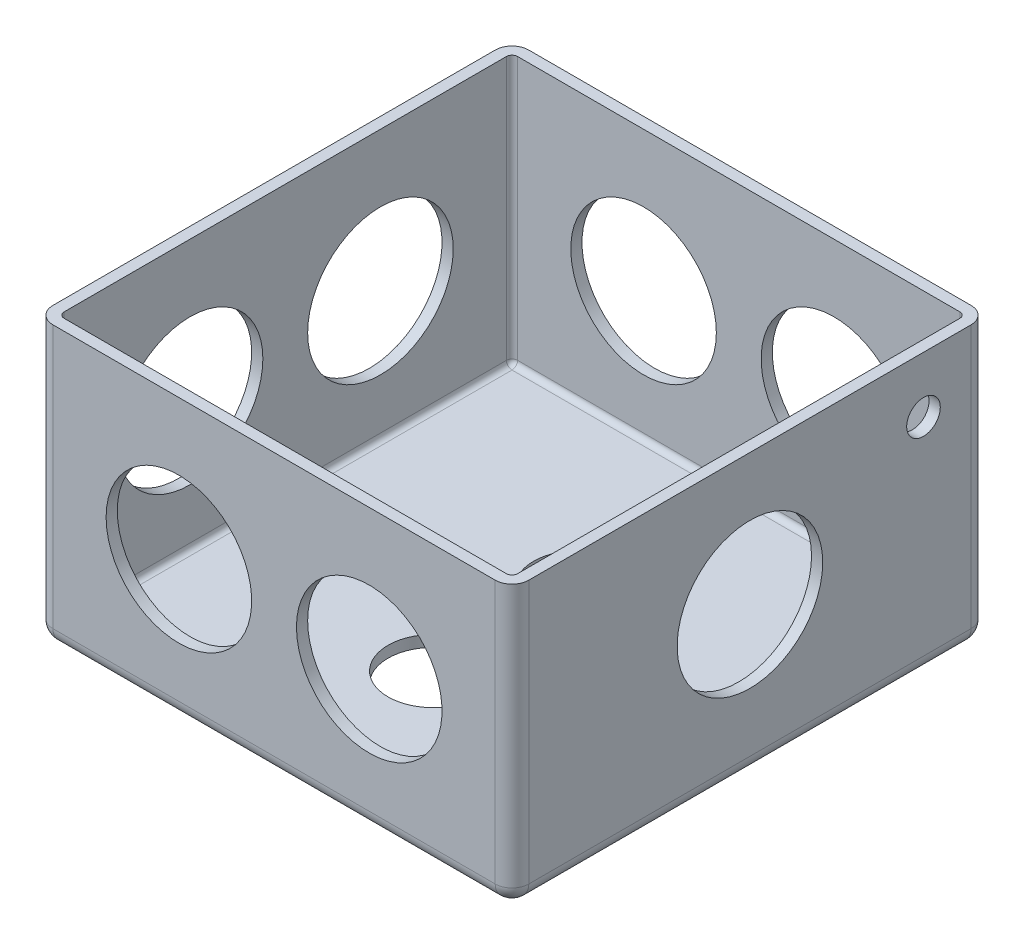
SolidWorks part; units mm, degrees
material "ABS"
ref_plane "Front Plane" through (0, 0, 0) normal (0, 0, 1) x (1, 0, 0)
ref_plane "Top Plane" through (0, 0, 0) normal (0, 1, 0) x (1, 0, 0)
ref_plane "Right Plane" through (0, 0, 0) normal (1, 0, 0) x (0, 0, -1)
sketch "Sketch1" plane through (0, 0, 0) normal (0, 1, 0) x (1, 0, 0)
  line L1 (-42.5, 42.5) -> (42.5, 42.5)
  line L2 (-42.5, 42.5) -> (-42.5, -42.5)
  line L3 (-42.5, -42.5) -> (42.5, -42.5)
  line L4 (42.5, 42.5) -> (42.5, -42.5)
  line L5 (-42.5, 42.5) -> (42.5, -42.5) construction
  line L6 (-42.5, -42.5) -> (42.5, 42.5) construction
  point P0 (0, 0)
  dimension "D1" = 85
  dimension "D2" = 85
extrude "Boss-Extrude1" add sketch "Sketch1" along normal blind 50
fillet "Fillet1" radius 3 8 edges at (-42.5, 25, -42.5) (-42.5, 25, 42.5) (42.5, 25, -42.5) (42.5, 25, 42.5) (-42.5, 0, 0) (0, 0, -42.5) (42.5, 0, 0) (0, 0, 42.5)
shell "Shell2" thickness 2
sketch "Sketch2" plane through (0, 0, 0) normal (0, -1, 0) x (1, 0, 0)
  line L1 (0, 14.1327) -> (0, -11.8673) construction
  circle A2 centre (0, 14.1327) radius 8
  circle A3 centre (0, -11.8673) radius 8
  point P4 (0, 0)
  point P11 (0, 1.1327)
  dimension "D2" = 16
  dimension "D3" = 26
  dimension "D1" = 16
extrude "Cut-Extrude1" cut sketch "Sketch2" against normal blind 50
sketch "Sketch3" plane through (0, 0, 42.5) normal (0, 0, 1) x (1, 0, 0)
  line L0 (17, 25) -> (-17, 25) construction
  line L2 (-42.5, 3) -> (-42.5, 50) construction
  circle A0 centre (-17, 25) radius 13
  circle A1 centre (17, 25) radius 13
  point P3 (0, 25)
  dimension "D2" = 26
  dimension "D3" = 26
  dimension "D1" = 34
  dimension "D4" = 25
  dimension "D5" = 42.5
extrude "Cut-Extrude2" cut sketch "Sketch3" against normal through all both and the other way through all
sketch "Sketch4" plane through (42.5, 0, 0) normal (1, 0, 0) x (0, 0, -1)
  line L0 (-39.5, 50) -> (39.5, 50) construction
  circle A0 centre (0, 26.5) radius 13
  circle A1 centre (30.9979, 40) radius 3
  dimension "D1" = 26
  dimension "D2" = 6
  dimension "D3" = 10
extrude "Cut-Extrude3" cut sketch "Sketch4" against normal blind 50
sketch "Sketch5" plane through (-42.5, 0, 0) normal (-1, 0, 0) x (0, 0, 1)
  line L0 (17, 25) -> (-17, 25) construction
  line L1 (-42.5, 3) -> (-42.5, 50) construction
  circle A0 centre (-17, 25) radius 13
  circle A1 centre (17, 25) radius 13
  point P3 (0, 25)
  dimension "D1" = 26
  dimension "D3" = 26
  dimension "D2" = 34
  dimension "D4" = 25
  dimension "D5" = 42.5
extrude "Cut-Extrude4" cut sketch "Sketch5" against normal blind 50
